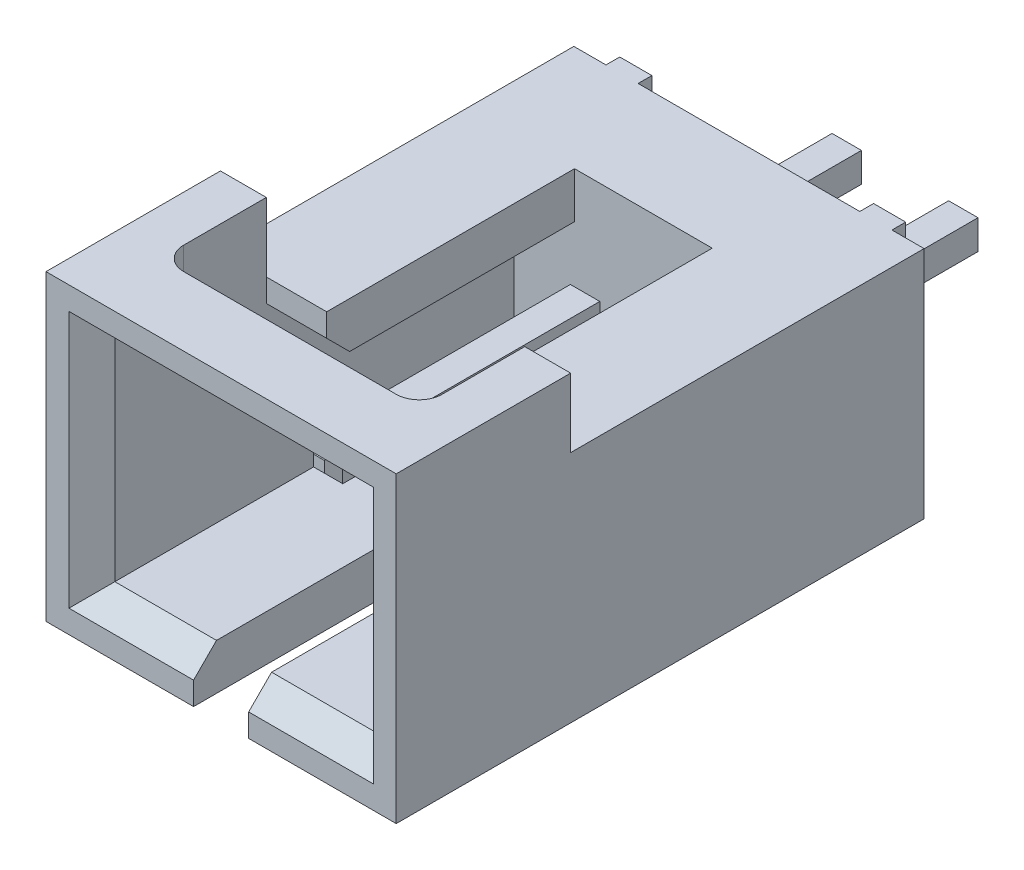
SolidWorks part; units mm, degrees
ref_plane "Front" through (0, 0, 0) normal (0, 0, 1) x (1, 0, 0)
ref_plane "Top" through (0, 0, 0) normal (0, 1, 0) x (1, 0, 0)
ref_plane "Right" through (0, 0, 0) normal (1, 0, 0) x (0, 0, -1)
sketch "Эскиз1" plane through (0, 0, 0) normal (0, 1, 0) x (1, 0, 0)
  line L0 (-2.415, -0.3) -> (2.415, -0.3)
  line L1 (2.415, -0.3) -> (2.415, 0)
  line L2 (2.415, 0) -> (3.115, 0)
  line L3 (3.115, 0) -> (3.115, -0.3)
  line L4 (3.115, -0.3) -> (3.815, -0.3)
  line L5 (3.815, -0.3) -> (3.815, -11.8)
  line L6 (3.815, -11.8) -> (-3.815, -11.8)
  line L7 (-3.815, -11.8) -> (-3.815, -0.3)
  line L8 (-3.815, -0.3) -> (-3.115, -0.3)
  line L9 (-3.115, -0.3) -> (-3.115, 0)
  line L10 (-3.115, 0) -> (-2.415, 0)
  line L11 (-2.415, 0) -> (-2.415, -0.3)
  line L12 (0, -0.3) -> (0, 0) construction
  line L13 (0, -11.8) -> (0, -0.3) construction
  dimension "D2" = 7.63
  dimension "D3" = 0.7
  dimension "D1" = 11.8
  dimension "D4" = 0.3
  dimension "D5" = 0.7
extrude "Бобышка-Вытянуть1" add sketch "Эскиз1" along normal mid plane 5.1
sketch "Эскиз2" plane through (0, 0, 11.8) normal (0, 0, 1) x (1, 0, 0)
  line L0 (-2.815, 1.55) -> (-2.815, -1.55)
  line L2 (2.815, -1.55) -> (2.815, 1.55)
  line L3 (2.815, 1.55) -> (1.5, 1.55)
  line L4 (1.5, 1.55) -> (1.5, 2.55)
  line L6 (1.5, 2.55) -> (-1.5, 2.55)
  line L7 (-1.5, 2.55) -> (-1.5, 1.55)
  line L8 (-1.5, 1.55) -> (-2.815, 1.55)
  line L9 (2.815, -1.55) -> (0.6, -1.55)
  line L10 (0.6, -1.55) -> (0.6, -2.55)
  line L11 (-3.815, -2.55) -> (3.815, -2.55) construction
  line L12 (0.6, -2.55) -> (-0.6, -2.55)
  line L13 (-0.6, -2.55) -> (-0.6, -1.55)
  line L14 (-0.6, -1.55) -> (-2.815, -1.55)
  line L15 (2.815, 1.55) -> (3.815, 1.55) construction
  line L16 (3.815, 2.55) -> (3.815, -2.55) construction
  line L17 (-2.815, 1.55) -> (-3.815, 1.55) construction
  line L18 (-3.815, 2.55) -> (-3.815, -2.55) construction
  line L19 (-3.815, 2.55) -> (3.815, 2.55) construction
  point P7 (0, 2.55)
  point P8 (0, 2.55)
  point P20 (0, -2.55)
  dimension "D1" = 1.2
  dimension "D2" = 3
  dimension "D3" = 1
  dimension "D4" = 3.815
extrude "Вырез-Вытянуть1" cut sketch "Эскиз2" against normal offset from surface (9.2 mm away) 2.3 up to face at (0, 0, 0.3)
sketch "Эскиз3" plane through (0, 0, 11.8) normal (0, 0, 1) x (1, 0, 0)
  line L0 (-3.815, 2.55) -> (-3.815, 4.05)
  line L1 (-3.815, 2.55) -> (-1.5, 2.55) construction
  line L2 (-3.815, 4.05) -> (3.815, 4.05)
  line L3 (3.815, 4.05) -> (3.815, 2.55)
  line L5 (3.815, 2.55) -> (2.815, 2.55)
  line L6 (2.815, 2.55) -> (2.815, 3.05)
  line L7 (2.815, 3.05) -> (-2.815, 3.05)
  line L8 (-2.815, 3.05) -> (-2.815, 2.55)
  line L9 (-2.815, 2.55) -> (-3.815, 2.55)
  line L10 (0, 0) -> (0, 3.05) construction
  line L11 (0, 3.05) -> (0, 4.05) construction
  line L12 (2.815, 1.55) -> (2.815, 2.55) construction
  line L15 (1.5, 2.55) -> (3.815, 2.55) construction
  line L16 (2.815, 1.55) -> (1.5, 1.55) construction
  line L17 (0.6, -2.55) -> (3.815, -2.55) construction
  dimension "D1" = 7.63
  dimension "D2" = 6.6
extrude "Бобышка-Вытянуть2" add sketch "Эскиз3" against normal blind 3.8
sketch "Эскиз4" plane through (0, 0, 11.8) normal (0, 0, 1) x (1, 0, 0)
  line L0 (-2.815, 2.55) -> (-2.815, 1.55)
  line L1 (-1.5, 1.55) -> (-2.815, 1.55) construction
  line L2 (-2.815, 1.55) -> (2.815, 1.55)
  line L3 (2.815, 1.55) -> (1.5, 1.55) construction
  line L4 (2.815, 1.55) -> (2.815, 2.55)
  line L5 (2.815, 2.55) -> (-2.815, 2.55)
extrude "Вырез-Вытянуть2" cut sketch "Эскиз4" against normal up to surface (3.8 mm away) up to face at (0, 3.05, 8)
sketch "Эскиз5" plane through (0, 4.05, 0) normal (0, 1, 0) x (1, 0, 0)
  line L0 (2.815, -8) -> (2.815, -9.8)
  line L1 (3.815, -8) -> (-3.815, -8) construction
  line L2 (2.315, -10.3) -> (-2.315, -10.3)
  line L3 (-2.815, -9.8) -> (-2.815, -8)
  line L4 (-2.815, -8) -> (2.815, -8)
  line L5 (3.815, -11.8) -> (-3.815, -11.8) construction
  arc A0 (2.815, -9.8) -> (2.315, -10.3) centre (2.315, -9.8) cw
  arc A1 (-2.315, -10.3) -> (-2.815, -9.8) centre (-2.315, -9.8) cw
  dimension "D1" = 1.5
  dimension "D2" = 0.5
extrude "Вырез-Вытянуть3" cut sketch "Эскиз5" against normal up to next
chamfer "Фаска1" distance 0.5 angle 45 7 edges at (1.7075, -1.55, 11.8) (2.815, 0.75, 11.8) (-1.7075, -1.55, 11.8) (-2.815, 0.75, 11.8) (0, 3.05, 11.8) (-2.1575, 1.55, 8) (2.1575, 1.55, 8)
sketch "Эскиз6" plane through (0, 0, 0.3) normal (0, 0, 1) x (1, 0, 0)
  line L0 (0, 0) -> (1.27, 0) construction
  line L1 (1.59, -0.32) -> (0.95, -0.32)
  line L2 (1.59, -0.32) -> (1.59, 0.32)
  line L3 (1.59, 0.32) -> (0.95, 0.32)
  line L4 (0.95, -0.32) -> (0.95, 0.32)
  line L5 (1.59, -0.32) -> (0.95, 0.32) construction
  line L6 (1.59, 0.32) -> (0.95, -0.32) construction
  line L7 (3.815, 2.55) -> (3.815, -2.55) construction
  point P0 (1.27, 0)
  dimension "D1" = 0.64
  dimension "D2" = 0.64
  dimension "D3" = 2.545
extrude "Бобышка-Вытянуть3" add sketch "Эскиз6" along normal offset from surface 3.4 and the other way offset from surface (3.6 mm away) 3.3 up to face at (0, -0.2667, 11.8) other way up to face at (2.765, 0, 0)
chamfer "Фаска2" distance 0.2 angle 45 8 edges at (0.95, 0, 8.4) (1.27, 0.32, 8.4) (1.59, 0, 8.4) (1.27, -0.32, 8.4) (1.27, -0.32, -3.3) (1.59, 0, -3.3) (1.27, 0.32, -3.3) (0.95, 0, -3.3)
pattern_linear "Линейный массив1" count 2 spacing 2.54 along (-1, 0, 0) of "Бобышка-Вытянуть3", "Фаска2"
equation "\"Pins\"= 2"
equation "\"B\"= \"Pins\" * 2.54мм + 2.55мм"
equation "\"D2@Эскиз1\"= \"B\""
equation "\"D1@Линейный массив1\"= \"Pins\""
